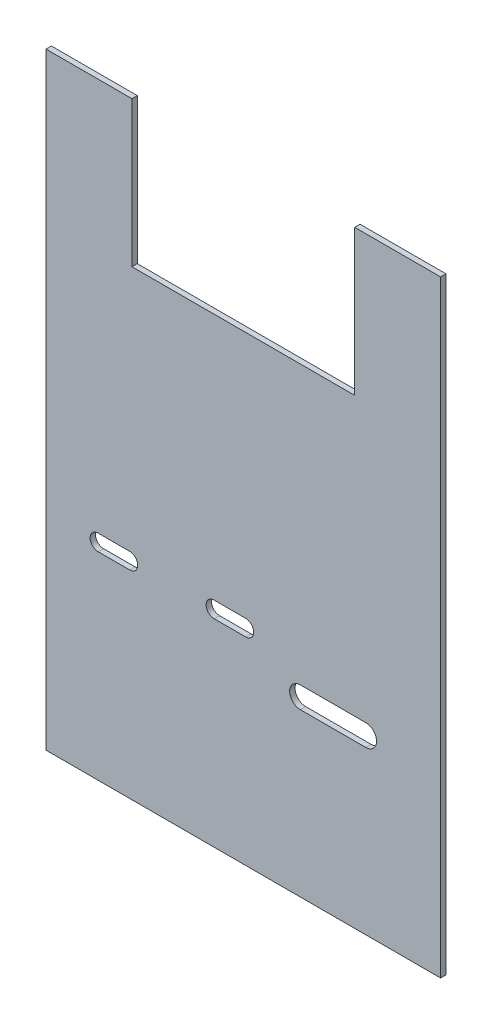
SolidWorks part; units mm, degrees
ref_plane "前视基准面" through (0, 0, 0) normal (0, 0, 1) x (1, 0, 0)
ref_plane "上视基准面" through (0, 0, 0) normal (0, 1, 0) x (1, 0, 0)
ref_plane "右视基准面" through (0, 0, 0) normal (1, 0, 0) x (0, 0, -1)
sketch "草图1" plane through (0, 0, 0) normal (0, 0, 1) x (1, 0, 0)
  line L0 (-83, 92.1192) -> (-115, 92.1192) construction
  line L1 (-83, 62.1192) -> (0, 62.1192)
  line L2 (-115, 62.1192) -> (-115, -109.8808)
  line L3 (-115, -109.8808) -> (32, -109.8808)
  line L4 (32, 62.1192) -> (32, -109.8808)
  line L5 (0, -109.8808) -> (32, -109.8808) construction
  line L6 (0, 92.1192) -> (0, -109.8808) construction
  line L7 (-115, 116.3427) -> (-83, 116.3427)
  line L8 (-115, 116.3427) -> (-115, 62.1192)
  line L10 (-83, 116.3427) -> (-83, 62.1192)
  line L11 (32, 116.3427) -> (0, 116.3427)
  line L12 (32, 116.3427) -> (32, 62.1192)
  line L14 (0, 116.3427) -> (0, 62.1192)
  dimension "D1" = 30
extrude "凸台-拉伸1" add sketch "草图1" along normal blind 2
sketch "草图2" plane through (0, 0, 2) normal (0, 0, 1) x (1, 0, 0)
  line L0 (-95.5727, -33.1357) -> (-83.8361, -33.1357) construction
  line L3 (-52.3582, -33.1357) -> (-40.6216, -33.1357) construction
  line L7 (-20.2275, -45.4311) -> (4.131, -45.4311) construction
  line L8 (-20.2275, -41.4311) -> (4.131, -41.4311)
  line L9 (-20.2275, -49.4311) -> (4.131, -49.4311)
  line L10 (-95.5727, -30.1357) -> (-83.8361, -30.1357)
  line L11 (-95.5727, -36.1357) -> (-83.8361, -36.1357)
  line L12 (-52.3582, -30.1357) -> (-40.6216, -30.1357)
  line L13 (-52.3582, -36.1357) -> (-40.6216, -36.1357)
  arc A4 (-20.2275, -41.4311) -> (-20.2275, -49.4311) centre (-20.2275, -45.4311) ccw
  arc A5 (4.131, -49.4311) -> (4.131, -41.4311) centre (4.131, -45.4311) ccw
  arc A6 (-95.5727, -30.1357) -> (-95.5727, -36.1357) centre (-95.5727, -33.1357) ccw
  arc A7 (-83.8361, -36.1357) -> (-83.8361, -30.1357) centre (-83.8361, -33.1357) ccw
  arc A8 (-52.3582, -30.1357) -> (-52.3582, -36.1357) centre (-52.3582, -33.1357) ccw
  arc A9 (-40.6216, -36.1357) -> (-40.6216, -30.1357) centre (-40.6216, -33.1357) ccw
  point P2 (-89.7044, -33.1357)
  point P11 (-46.4899, -33.1357)
  point P16 (-8.0482, -45.4311)
  dimension "D2" = 4
  dimension "D1" = 3
extrude "切除-拉伸1" cut sketch "草图2" against normal blind 2
